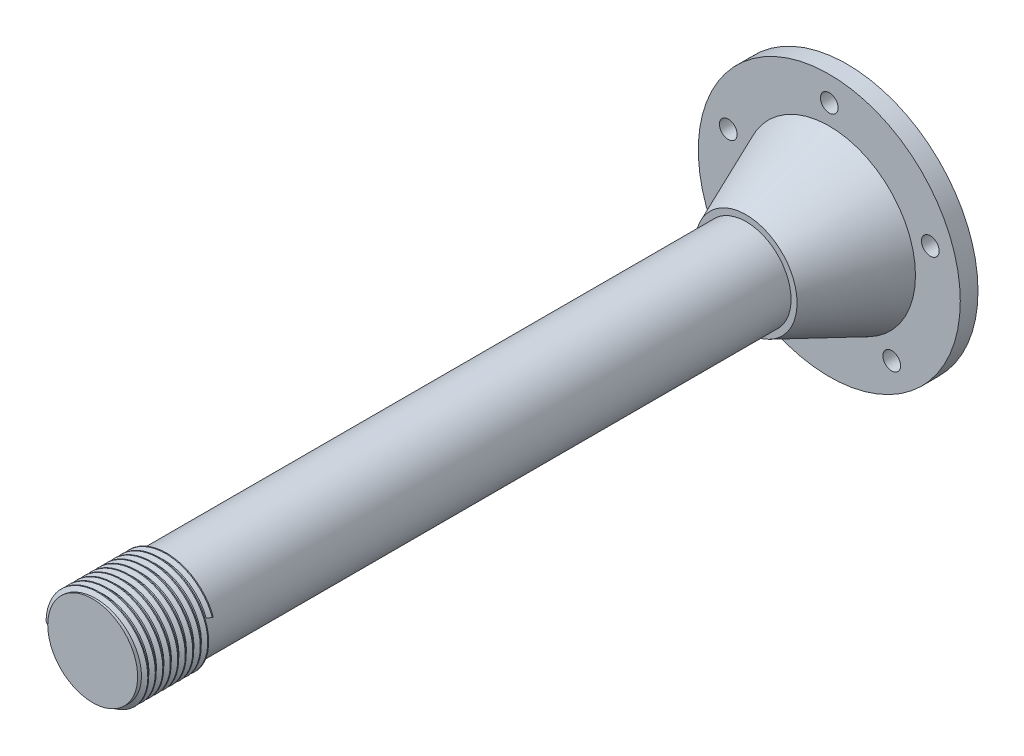
SolidWorks part; units mm, degrees
material "AISI 1020 Steel, Cold Rolled"
ref_plane "Front Plane" through (0, 0, 0) normal (0, 0, 1) x (1, 0, 0)
ref_plane "Top Plane" through (0, 0, 0) normal (0, 1, 0) x (1, 0, 0)
ref_plane "Right Plane" through (0, 0, 0) normal (1, 0, 0) x (0, 0, -1)
sketch "Sketch1" plane through (0, 0, 0) normal (0, 0, 1) x (1, 0, 0)
  circle A0 centre (0, 0) radius 37
  circle A1 centre (0, 0) radius 30 construction
  circle A2 centre (0, 30) radius 2.5
  circle A3 centre (28.5317, 9.2705) radius 2.5
  circle A4 centre (17.6336, -24.2705) radius 2.5
  circle A5 centre (-17.6336, -24.2705) radius 2.5
  circle A6 centre (-28.5317, 9.2705) radius 2.5
  point P16 (0, 0)
  dimension "D1" = 74
  dimension "D2" = 5
  dimension "D3" = 60
  dimension "D4" = 5
extrude "Boss-Extrude1" add sketch "Sketch1" along normal mid plane 5
sketch "Sketch2" plane through (0, 0, 0) normal (0, 0, 1) x (1, 0, 0)
  circle A0 centre (0, 0) radius 25.4
  dimension "D1" = 50.8
extrude "Boss-Extrude2" add sketch "Sketch2" along normal blind 26 draft 22.945 contours A0
ref_plane "Plane1" through (0, 0, 26) normal (0, 0, 1) x (1, 0, 0)
sketch "Sketch3" plane through (0, 0, 26) normal (0, 0, 1) x (1, 0, 0)
  circle A0 centre (0, 0) radius 12.7
  dimension "D1" = 25.4
extrude "Boss-Extrude3" add sketch "Sketch3" along normal blind 184.55
thread "Thread1" pitch 2.1167 profile "Thread Profile1" start angle 0, offset 0, length 20, pitch 2.1167, diameter 25.4
ref_plane "Plane2" through (-12.7, 0, 210.55) normal (0, -1, 0) x (-1, 0, 0)
sketch "Thread Profile1" plane through (-12.7, 0, 210.55) normal (0, -1, 0) x (-1, 0, 0)
  line L0 (0, 0) -> (0, 2.1167) construction
  line L1 (0, 0) -> (1.1457, 0.6615)
  line L2 (1.1457, 0.6615) -> (1.1457, 0.926)
  line L3 (1.1457, 0.926) -> (0, 1.5875)
  line L4 (1.1457, 0.7937) -> (0, 0.7937) construction
  line L11 (0, 0) -> (0, 1.5875)
  point P2 (0, 0)
  dimension "Pitch" = 2.1167
  dimension "Profile_Angle" = 60
  dimension "Profile_Land" = 0.2646
  dimension "Profile_Height" = 1.1457
